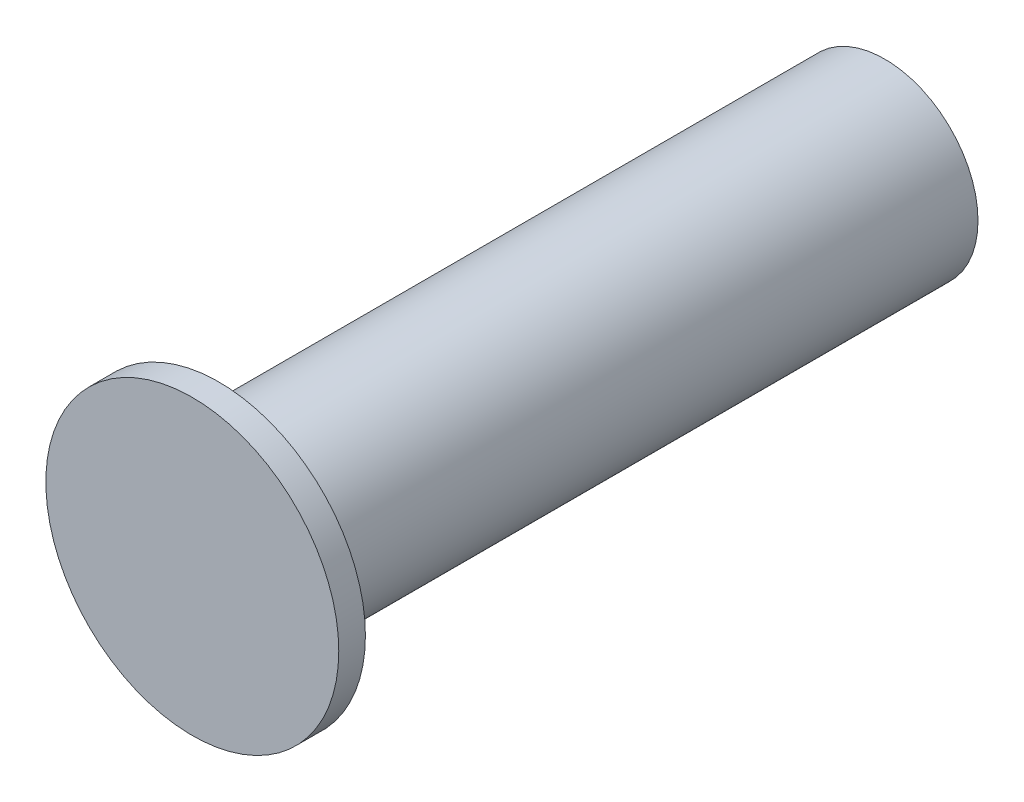
SolidWorks part; units mm, degrees
ref_plane "Front Plane" through (0, 0, 0) normal (0, 0, 1) x (1, 0, 0)
ref_plane "Top Plane" through (0, 0, 0) normal (0, 1, 0) x (1, 0, 0)
ref_plane "Right Plane" through (0, 0, 0) normal (1, 0, 0) x (0, 0, -1)
sketch "Sketch1" plane through (0, 0, 0) normal (0, 0, 1) x (1, 0, 0)
  circle A0 centre (0, 0) radius 2.794
  dimension "D1" = 5.588
extrude "Boss-Extrude1" add sketch "Sketch1" along normal blind 0.508
sketch "Sketch2" plane through (0, 0, 0) normal (0, 0, -1) x (-1, 0, 0)
  circle A0 centre (0, 0) radius 1.7795
extrude "Boss-Extrude2" add sketch "Sketch2" along normal blind 12.7
